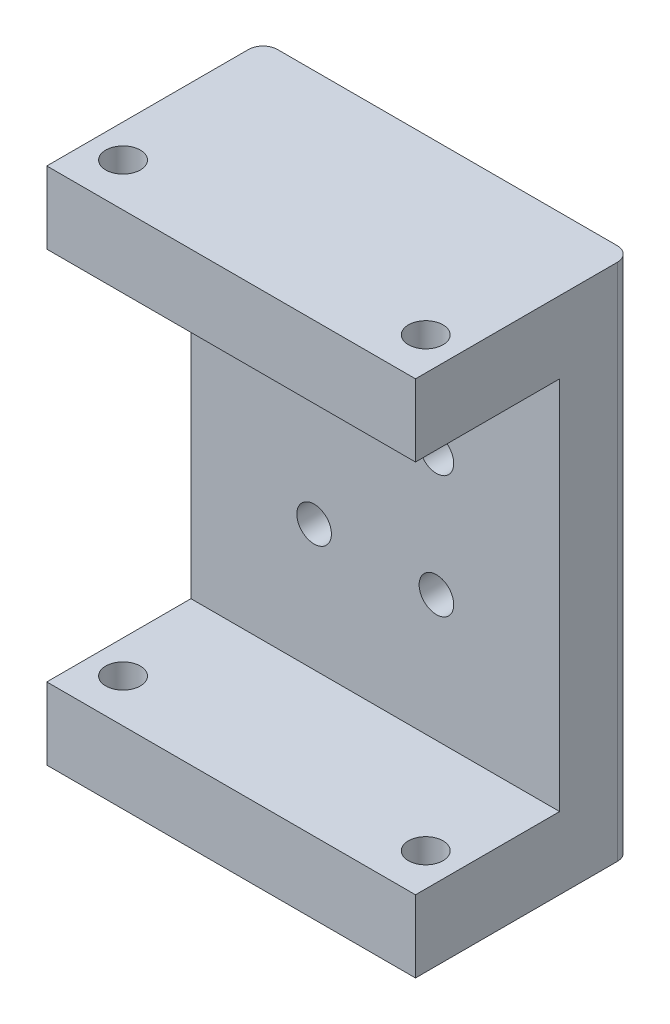
SolidWorks part; units mm, degrees
ref_plane "正面" through (0, 0, 0) normal (0, 0, 1) x (1, 0, 0)
ref_plane "平面" through (0, 0, 0) normal (0, 1, 0) x (1, 0, 0)
ref_plane "右側面" through (0, 0, 0) normal (1, 0, 0) x (0, 0, -1)
sketch "ｽｹｯﾁ1" plane through (0, 0, 0) normal (0, 0, 1) x (1, 0, 0)
  line L1 (-12.79, 18) -> (12.79, 18)
  line L2 (-12.79, 18) -> (-12.79, -18)
  line L3 (-12.79, -18) -> (12.79, -18)
  line L4 (12.79, 18) -> (12.79, -18)
  line L5 (-12.79, 18) -> (12.79, -18) construction
  line L6 (-12.79, -18) -> (12.79, 18) construction
  point P0 (0, 0)
  dimension "D1" = 36
  dimension "D2" = 25.58
extrude "ﾎﾞｽ - 押し出し1" add sketch "ｽｹｯﾁ1" along normal blind 15
sketch "ｽｹｯﾁ2" plane through (-12.79, 0, 0) normal (-1, 0, 0) x (0, 0, 1)
  line L0 (15, 18) -> (15, -18) construction
  line L1 (15, 13) -> (5, 13)
  line L2 (15, 13) -> (15, -13)
  line L3 (15, -13) -> (5, -13)
  line L4 (5, 13) -> (5, -13)
  line L5 (15, 18) -> (0, 18) construction
  line L6 (0, 18) -> (0, -18) construction
  point P6 (5, 0)
  dimension "D1" = 5
  dimension "D2" = 5
extrude "ｶｯﾄ - 押し出し1" cut sketch "ｽｹｯﾁ2" against normal through all
hole_wizard "M2 すきま穴1" positions "ｽｹｯﾁ3" profile "ｽｹｯﾁ4" hole size "M2" standard "JIS" end condition through all
sketch "ｽｹｯﾁ3" plane through (0, 18, 0) normal (0, 1, 0) x (1, 0, 0)
  line L1 (-10.5, -12) -> (10.5, -12)
  line L3 (12.79, -15) -> (-12.79, -15) construction
  point P0 (-10.5, -12)
  point P2 (10.5, -12)
  point P15 (0, -15)
  point P16 (0, -12)
  dimension "D1" = 21
  dimension "D2" = 3
sketch "ｽｹｯﾁ4" plane through (-10.5, 18, 12) normal (1, 0, 0) x (0, 0, 1)
  line L0 (0, 0) -> (0, 36)
  line L1 (0, 36) -> (1.2, 36)
  line L2 (1.2, 36) -> (1.2, 0)
  line L5 (1.2, 0) -> (0, 0)
  line L11 (0, -6.35) -> (0, 107.95) construction
  dimension "通し穴の直径" = 2.4
  dimension "通し穴の深さ" = 36
fillet "ﾌｨﾚｯﾄ1" radius 1 2 edges at (12.79, 0, 0) (-12.79, 0, 0)
sketch "ｽｹｯﾁ5" plane through (0, 0, 0) normal (0, 0, -1) x (-1, 0, 0)
  circle A0 centre (0, 0) radius 4.25
  dimension "D1" = 8.5
extrude "ｶｯﾄ - 押し出し2" cut sketch "ｽｹｯﾁ5" against normal blind 1.5
hole_wizard "M2 すきま穴2" positions "ｽｹｯﾁ8" profile "ｽｹｯﾁ9" hole size "M2" standard "JIS" end condition through all
sketch "ｽｹｯﾁ8" plane through (0, 0, 5) normal (0, 0, 1) x (1, 0, 0)
  line L8 (4.2426, 4.2426) -> (-4.2426, 4.2426)
  line L9 (4.2426, 4.2426) -> (4.2426, -4.2426)
  line L10 (4.2426, -4.2426) -> (-4.2426, -4.2426)
  line L11 (-4.2426, 4.2426) -> (-4.2426, -4.2426)
  point P90 (4.2426, 4.2426)
  point P91 (-4.2426, -4.2426)
  point P216 (4.2426, -4.2426)
  point P217 (-4.2426, 4.2426)
  point P219 (4.2426, 0)
  point P221 (0, -4.2426)
  dimension "D1" = 6
sketch "ｽｹｯﾁ9" plane through (4.2426, 4.2426, 5) normal (1, 0, 0) x (0, -1, 0)
  line L0 (0, 0) -> (0, 5)
  line L1 (0, 5) -> (1.2, 5)
  line L2 (1.2, 5) -> (1.2, 0)
  line L5 (1.2, 0) -> (0, 0)
  line L11 (0, -6.35) -> (0, 107.95) construction
  dimension "通し穴の直径" = 2.4
  dimension "通し穴の深さ" = 5
